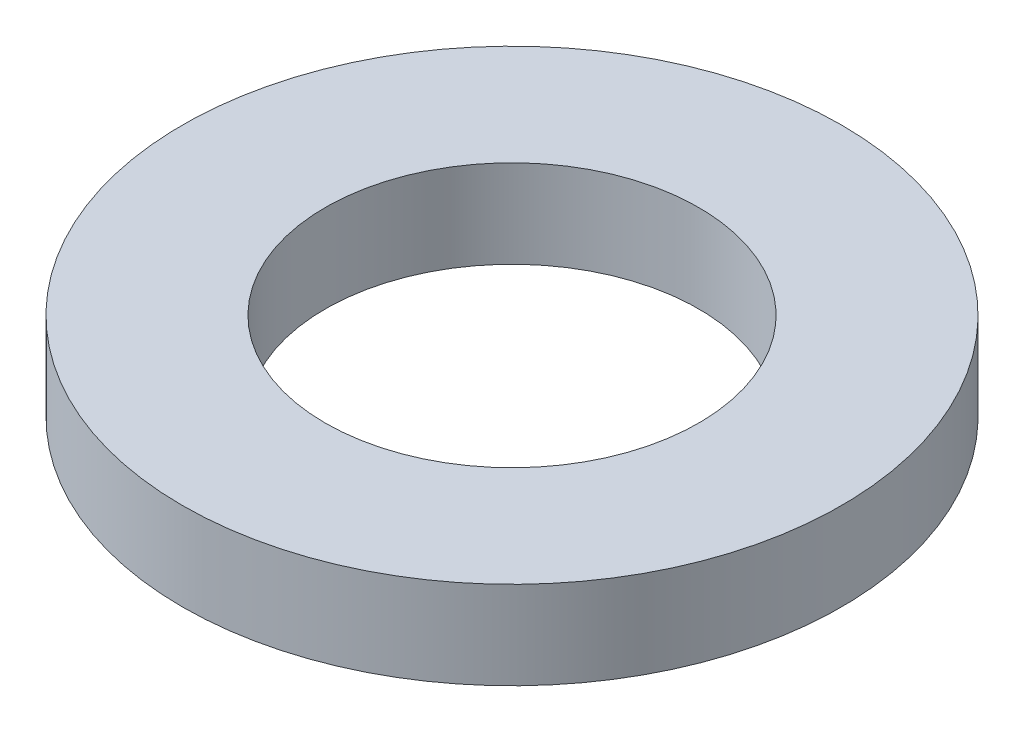
SolidWorks part; units mm, degrees
ref_plane "前视基准面" through (0, 0, 0) normal (0, 0, 1) x (1, 0, 0)
ref_plane "上视基准面" through (0, 0, 0) normal (0, 1, 0) x (1, 0, 0)
ref_plane "右视基准面" through (0, 0, 0) normal (1, 0, 0) x (0, 0, -1)
sketch "草图1" plane through (0, 0, 0) normal (0, 1, 0) x (1, 0, 0)
  circle A0 centre (0, 0) radius 15
  circle A1 centre (0, 0) radius 8.5
  dimension "D1" = 17
  dimension "D2" = 30
extrude "凸台-拉伸1" add sketch "草图1" along normal blind 4
